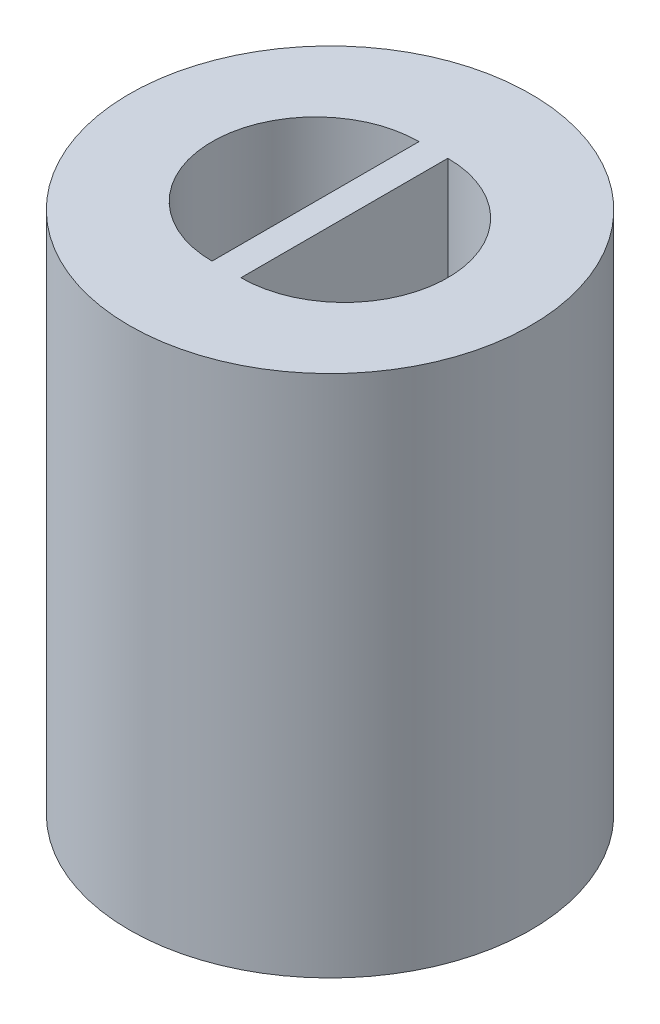
SolidWorks part; units mm, degrees
ref_plane "Front Plane" through (0, 0, 0) normal (0, 0, 1) x (1, 0, 0)
ref_plane "Top Plane" through (0, 0, 0) normal (0, 1, 0) x (1, 0, 0)
ref_plane "Right Plane" through (0, 0, 0) normal (1, 0, 0) x (0, 0, -1)
sketch "Sketch1" plane through (0, 0, 0) normal (0, 1, 0) x (1, 0, 0)
  circle A0 centre (0, 0) radius 5.75
  dimension "D1" = 11.5
extrude "Boss-Extrude1" add sketch "Sketch1" along normal blind 15
sketch "Sketch6" plane through (0, 15, 0) normal (0, 1, 0) x (1, 0, 0)
  line L4 (0.41, 2.9647) -> (0.41, -2.9647)
  line L5 (-0.4164, 2.9656) -> (-0.4164, -2.9656)
  arc A3 (0.41, 2.9647) -> (0.41, -2.9647) centre (0.41, 0) cw
  arc A4 (-0.4164, 2.9656) -> (-0.4164, -2.9656) centre (-0.4164, 0) ccw
  dimension "D2" = 0.41
extrude "Cut-Extrude3" cut sketch "Sketch6" against normal blind 8
sketch "Sketch7" plane through (0, 0, 0) normal (0, 1, 0) x (1, 0, 0)
  circle A0 centre (0, 0) radius 1
  dimension "D1" = 2
extrude "Cut-Extrude4" cut sketch "Sketch7" along normal blind 6.5
